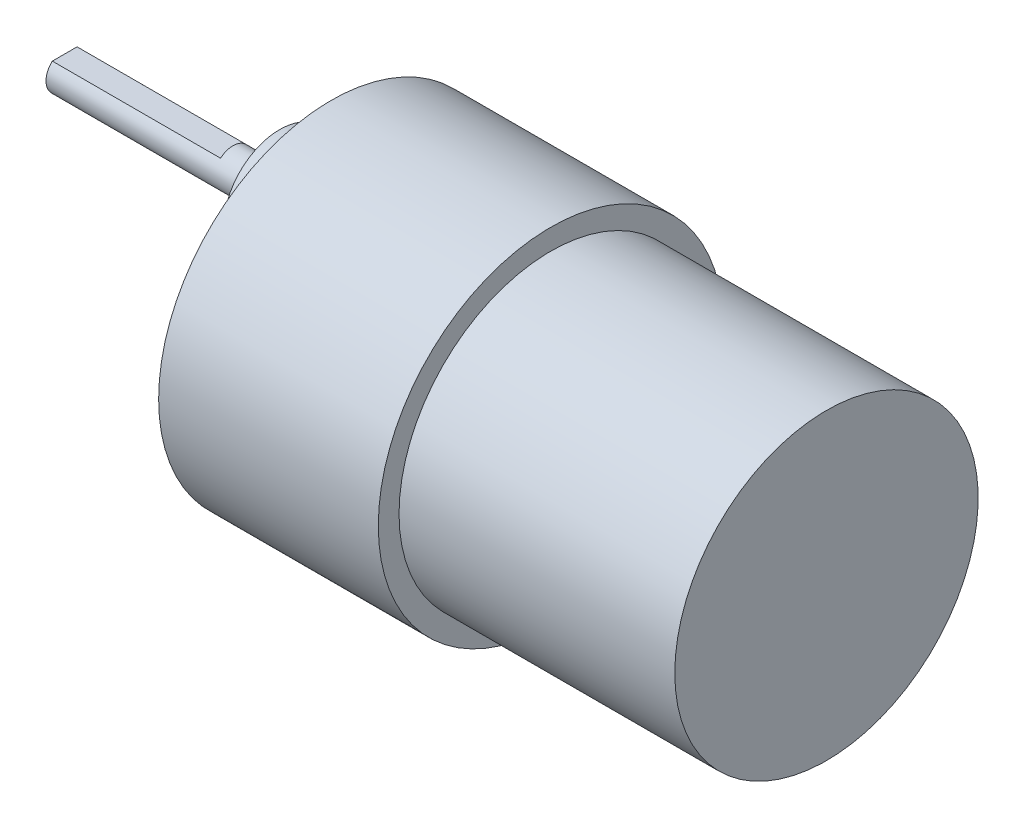
SolidWorks part; units mm, degrees
ref_plane "Front Plane" through (0, 0, 0) normal (0, 0, 1) x (1, 0, 0)
ref_plane "Top Plane" through (0, 0, 0) normal (0, 1, 0) x (1, 0, 0)
ref_plane "Right Plane" through (0, 0, 0) normal (1, 0, 0) x (0, 0, -1)
sketch "Sketch1" plane through (0, 0, 0) normal (0, 0, 1) x (1, 0, 0)
  line L1 (0, 0) -> (23.5, 0)
  line L2 (0, 0) -> (0, 18.45)
  line L3 (0, 18.45) -> (23.5, 18.45)
  line L4 (23.5, 0) -> (23.5, 18.45)
  line L5 (23.5, 16.23) -> (53, 16.23)
  line L6 (23.5, 16.23) -> (23.5, 0)
  line L7 (23.5, 0) -> (53, 0)
  line L8 (53, 16.23) -> (53, 0)
  dimension "D1" = 23.5
  dimension "D2" = 29.5
  dimension "D3" = 16.23
  dimension "D4" = 18.45
revolve "Revolve1" add sketch "Sketch1" angle 360 about L1
sketch "Sketch2" plane through (0, 0, 0) normal (-1, 0, 0) x (0, 0, 1)
  line L0 (0, 0) -> (0, 18.45) construction
  line L1 (0, 0) -> (7.75, 13.4234) construction
  circle A0 centre (0, 0) radius 15.5 construction
  circle A1 centre (0, 0) radius 18.45 construction
  point P1 (7.75, 13.4234)
  point P4 (15.5, 0)
  point P7 (7.75, -13.4234)
  point P8 (-7.75, -13.4234)
  point P9 (-15.5, 0)
  point P10 (-7.75, 13.4234)
  point P11 (0, 0)
  dimension "D1" = 31
  dimension "D3" = 30
  dimension "D2" = 6
hole_wizard "M3.5x0.6 Tapped Hole1" positions "Sketch3" profile "Sketch5" tap size "M3.5x0.6" standard "ANSI Metric"
sketch "Sketch3" plane through (0, 0, 0) normal (-1, 0, 0) x (0, 0, 1)
  point P0 (7.75, 13.4234)
  point P3 (15.5, 0)
  point P6 (7.75, -13.4234)
  point P9 (-7.75, -13.4234)
  point P12 (-15.5, 0)
  point P15 (-7.75, 13.4234)
sketch "Sketch5" plane through (0, 13.4234, 7.75) normal (0, 1, 0) x (0, 0, 1)
  line L0 (0, 0) -> (0, 4.3712)
  line L1 (0, 4.3712) -> (1.45, 3.5)
  line L2 (1.45, 3.5) -> (1.45, 0)
  line L5 (1.45, 0) -> (0, 0)
  line L10 (0, 4.3712) -> (-1.45, 3.5) construction
  line L11 (0, -6.35) -> (0, 107.95) construction
  dimension "Tap Drill Dia." = 2.9
  dimension "Tap Drill Depth" = 3.5
  dimension "Drill Angle" = 118
cosmetic thread "Hole Thread1" parameters "D1"=7, "D2"=3.5
cosmetic thread "Hole Thread2" parameters "D1"=7, "D2"=3.5
cosmetic thread "Hole Thread3" parameters "D1"=7, "D2"=3.5
cosmetic thread "Hole Thread4" parameters "D1"=7, "D2"=3.5
cosmetic thread "Hole Thread5" parameters "D1"=7, "D2"=3.5
cosmetic thread "Hole Thread6" parameters "D1"=7, "D2"=3.5
sketch "Sketch6" plane through (0, 0, 0) normal (-1, 0, 0) x (0, 0, 1)
  circle A0 centre (0, 7) radius 6
  dimension "D2" = 12
  dimension "D1" = 7
extrude "Boss-Extrude1" add sketch "Sketch6" along normal blind 5.5
sketch "Sketch7" plane through (-5.5, 0, 0) normal (-1, 0, 0) x (0, 0, 1)
  circle A0 centre (0, 7) radius 2
  dimension "D1" = 4
extrude "Boss-Extrude2" add sketch "Sketch7" along normal blind 23
sketch "Sketch8" plane through (-28.5, 0, 0) normal (-1, 0, 0) x (0, 0, 1)
  line L0 (-1.3229, 8.5) -> (1.3229, 8.5)
  circle A0 centre (0, 7) radius 2 construction
  circle A1 centre (0, 7) radius 2
  circle M2 centre (0, 7) radius 2
  dimension "D1" = 3.5
extrude "Cut-Extrude1" cut sketch "Sketch8" against normal blind 18 contours L0 M2
